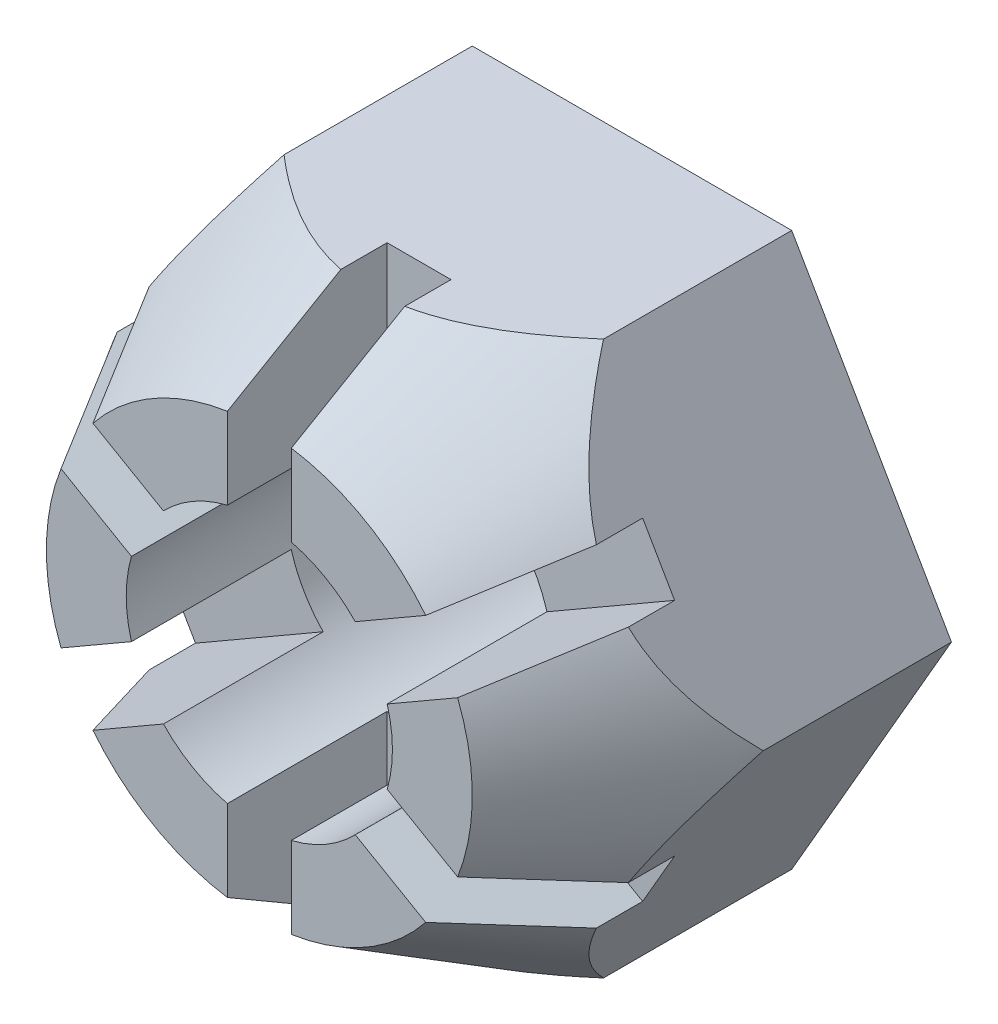
SolidWorks part; units mm, degrees
ref_plane "Front Plane" through (0, 0, 0) normal (0, 0, 1) x (1, 0, 0)
ref_plane "Top Plane" through (0, 0, 0) normal (0, 1, 0) x (1, 0, 0)
ref_plane "Right Plane" through (0, 0, 0) normal (1, 0, 0) x (0, 0, -1)
sketch "Sketch1" plane through (0, 0, 0) normal (0, 0, 1) x (1, 0, 0)
  line L2 (60, 0) -> (30, 51.9615)
  line L3 (30, 51.9615) -> (-30, 51.9615)
  line L4 (-30, 51.9615) -> (-60, 0)
  line L5 (-60, 0) -> (-30, -51.9615)
  line L6 (-30, -51.9615) -> (30, -51.9615)
  line L7 (30, -51.9615) -> (60, 0)
  circle A0 centre (0, 0) radius 51.9615 construction
  dimension "120" = 120
extrude "Boss-Extrude1" add sketch "Sketch1" along normal blind 70
sketch "Sketch2" plane through (0, 0, 70) normal (0, 0, 1) x (1, 0, 0)
  circle A0 centre (0, 0) radius 25
  dimension "50" = 50
extrude "Cut-Extrude1" cut sketch "Sketch2" against normal through all
cosmetic thread "Cosmetic Thread1" parameters "D2"=56
sketch "Sketch3" plane through (0, 0, 70) normal (0, 0, 1) x (1, 0, 0)
  circle A0 centre (0, 0) radius 40
  dimension "D1" = 80
extrude "Cut-Extrude2" cut sketch "Sketch3" against normal blind 70 draft 30 flip side to cut
sketch "Sketch6" plane through (0, 0, 70) normal (0, 0, 1) x (1, 0, 0)
  line L1 (6, -53.1106) -> (-6, -53.1106)
  line L2 (6, -53.1106) -> (6, -24.2693)
  line L3 (6, -24.2693) -> (-6, -24.2693)
  line L4 (-6, -53.1106) -> (-6, -24.2693)
  line L5 (6, -53.1106) -> (-6, -24.2693) construction
  line L6 (6, -24.2693) -> (-6, -53.1106) construction
  circle A0 centre (0, 0) radius 25 construction
  point P0 (0, -38.69)
  dimension "D1" = 12
extrude "Cut-Extrude3" cut sketch "Sketch6" against normal blind 30
pattern_circular "CirPattern1" count 6 over 360 about axis through (0, 0, 0) along (0, 0, 1) of "Cut-Extrude3"
